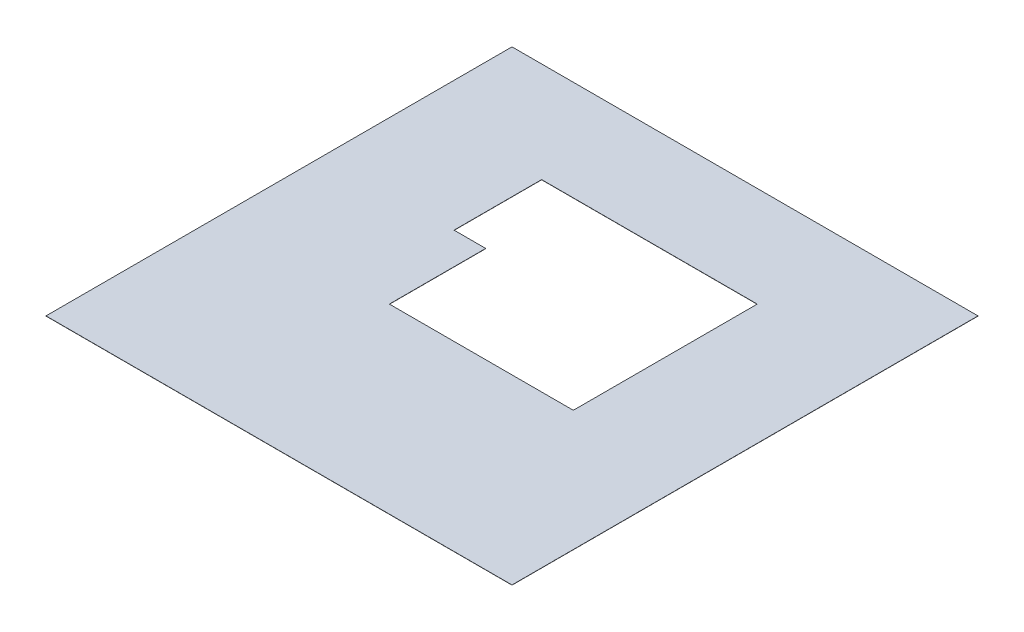
SolidWorks part; units mm, degrees
ref_plane "Front Plane" through (0, 0, 0) normal (0, 0, 1) x (1, 0, 0)
ref_plane "Top Plane" through (0, 0, 0) normal (0, 1, 0) x (1, 0, 0)
ref_plane "Right Plane" through (0, 0, 0) normal (1, 0, 0) x (0, 0, -1)
sketch "Sketch1" plane through (0, 0, 0) normal (0, 1, 0) x (1, 0, 0)
  line L0 (-11400, -11400) -> (-11400, 11400)
  line L1 (-11500, -11500) -> (11500, -11500)
  line L2 (-11500, -11500) -> (-11500, 11500)
  line L3 (-11500, 11500) -> (11500, 11500)
  line L4 (11500, -11500) -> (11500, 11500)
  line L5 (-11500, -11500) -> (11500, 11500) construction
  line L6 (-11500, 11500) -> (11500, -11500) construction
  line L7 (-11400, 11400) -> (11400, 11400)
  line L8 (11400, -11400) -> (11400, 11400)
  line L9 (-11400, -11400) -> (11400, -11400)
  line L10 (-3500, -2500) -> (5500, -2500)
  line L11 (5500, -2500) -> (5500, 6500)
  line L12 (5500, 6500) -> (-5050, 6500)
  line L13 (-5050, 6500) -> (-5050, 2215)
  line L14 (-5050, 2215) -> (-3500, 2215)
  line L15 (-3500, 2215) -> (-3500, -2500)
  line L16 (5370, 6370) -> (-4920, 6370)
  line L17 (-4920, 6370) -> (-4920, 2345)
  line L18 (-4920, 2345) -> (-3370, 2345)
  line L19 (-3370, 2345) -> (-3370, -2370)
  line L20 (-3370, -2370) -> (5370, -2370)
  line L21 (5370, -2370) -> (5370, 6370)
  line L22 (-3500, 2345) -> (-3500, 6370)
  line L23 (-3370, 2345) -> (-3370, 6370)
  line L24 (-3500, 2215) -> (-3500, 2345) construction
  line L25 (6400, 7400) -> (-5950, 7400)
  line L26 (-5950, 7400) -> (-5950, 1315)
  line L27 (-5950, 1315) -> (-4400, 1315)
  line L28 (-4400, 1315) -> (-4400, -2475.6293)
  line L29 (3617.6909, -3400) -> (6400, -3400)
  line L30 (6400, -3400) -> (6400, 7400)
  line L31 (-3500, -2500) -> (-4400, -2500)
  line L32 (3625, -2500) -> (3625, -3400)
  line L33 (-4400, -3400) -> (6400, -3400) construction
  line L34 (-4400, 1315) -> (-4400, -3400) construction
  point P0 (0, 0)
  point P34 (0, 0)
  dimension "D1" = 23000
  dimension "D2" = 90
  dimension "D4" = 10550
  dimension "D5" = 9000
  dimension "D6" = 9000
  dimension "D7" = 4285
  dimension "D8" = 9000
  dimension "D9" = 9000
  dimension "D10" = 6000
  dimension "D12" = 900
  dimension "D13" = 1875
  dimension "D14" = 900
  dimension "D3" = 100
  dimension "D11" = 130
extrude "Boss-Extrude1" add sketch "Sketch1" along normal blind 10
